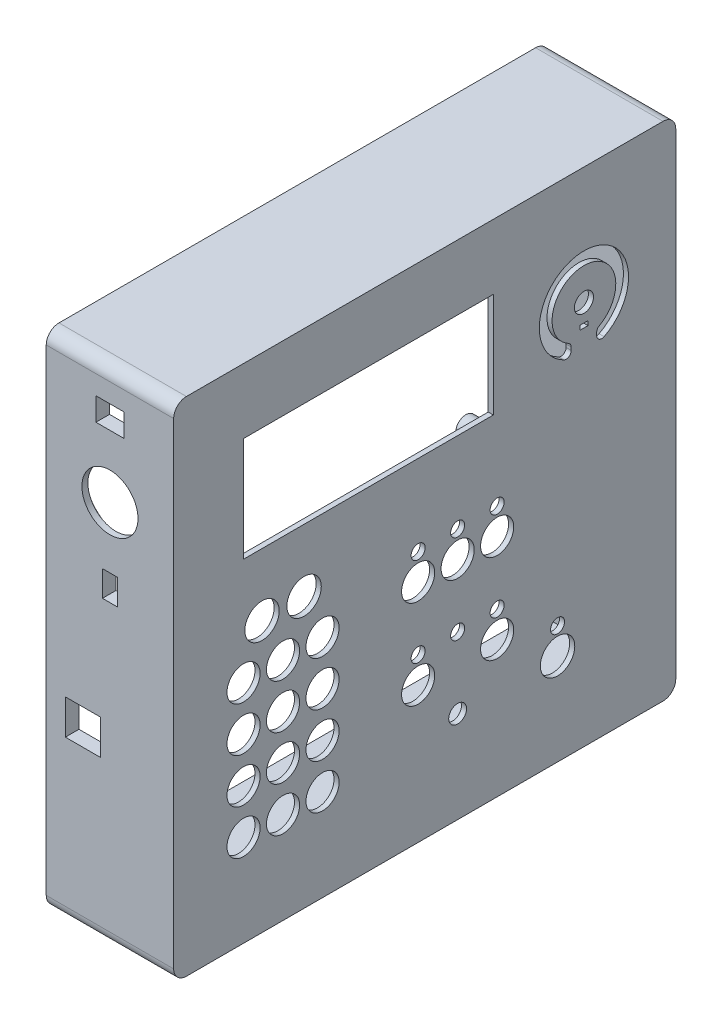
SolidWorks part; units mm, degrees
ref_plane "Front Plane" through (0, 0, 0) normal (0, 0, 1) x (1, 0, 0)
ref_plane "Top Plane" through (0, 0, 0) normal (0, 1, 0) x (1, 0, 0)
ref_plane "Right Plane" through (0, 0, 0) normal (1, 0, 0) x (0, 0, -1)
sketch "Sketch1" plane through (0, 0, 0) normal (1, 0, 0) x (0, 0, -1)
  line L0 (-106.2893, 98.5) -> (-106.2893, -98.5)
  line L1 (-227.2314, 0) -> (0, 0) construction
  line L2 (0, 0) -> (0, 137.3832) construction
  line L3 (-106.2893, -98.5) -> (-303.2893, -98.5)
  line L5 (-106.2893, 98.5) -> (-303.2893, 98.5)
  line L6 (-303.2893, -98.5) -> (-303.2893, 98.5)
  line L7 (-204.7893, 98.5) -> (-204.7893, -98.5) construction
  point P0 (-204.7893, 98.5)
  point P11 (-106.2893, 98.5)
  dimension "D1" = 98.5
  dimension "D2" = 197
  dimension "D3" = 197
  dimension "D4" = 204.7893
extrude "Boss-Extrude1" add sketch "Sketch1" along normal blind 50
sketch "Sketch6" plane through (0, 0, 0) normal (1, 0, 0) x (0, 0, -1)
  line L0 (-106.2893, 98.5) -> (-303.2893, 98.5) construction
  line L5 (0, 0) -> (-397.2484, 0) construction
  line L6 (0, 0) -> (0, 147.2873) construction
  line L7 (-106.2893, 98.5) -> (-303.2893, 98.5) construction
  line L8 (-297.9497, 93.5) -> (-110.9497, 93.5)
  line L9 (-297.9497, 93.5) -> (-297.9497, -93.5)
  line L10 (-297.9497, -93.5) -> (-110.9497, -93.5)
  line L11 (-110.9497, 93.5) -> (-110.9497, -93.5)
  line L13 (-204.4497, 98.5) -> (-204.4497, -141.7446) construction
  point P14 (-204.4497, 98.5)
  dimension "D1" = 187
  dimension "D2" = 187
  dimension "D3" = 93.5
  dimension "D4" = 110.9497
  dimension "D6" = 93.5
extrude "Cut-Extrude1" cut sketch "Sketch6" along normal blind 48
ref_plane "Plane2" through (48, 0, 0) normal (-1, 0, 0) x (0, 0, 1)
sketch "Sketch8" plane through (48, 0, 0) normal (-1, 0, 0) x (0, 0, 1)
  line L0 (0, 0) -> (304.4109, 0) construction
  line L1 (317.8268, 52.5) -> (90.3561, 52.5) construction
  line L2 (226.8693, 32) -> (226.8693, 82.5833) construction
  line L3 (275.8693, 32) -> (177.8693, 32)
  line L4 (275.8693, 32) -> (275.8693, 73)
  line L5 (275.8693, 73) -> (177.8693, 73)
  line L6 (177.8693, 32) -> (177.8693, 73)
  line L7 (276.1193, 22.5) -> (177.6193, 22.5) construction
  line L8 (276.1193, 22.5) -> (276.1193, 82.5) construction
  line L9 (276.1193, 82.5) -> (177.6193, 82.5) construction
  line L10 (177.6193, 22.5) -> (177.6193, 82.5) construction
  line L11 (303.2893, 98.5) -> (303.2893, -98.5) construction
  dimension "D8" = 27.42
  dimension "D1" = 41
  dimension "D2" = 20.5
  dimension "D3" = 98
  dimension "D4" = 98.5
  dimension "D5" = 60
  dimension "D6" = 49.25
  dimension "D7" = 30
  dimension "D10" = 52.5
extrude "Cut-Extrude2" cut sketch "Sketch8" against normal blind 25
sketch "Sketch9" plane through (48, 0, 0) normal (-1, 0, 0) x (0, 0, 1)
  line L0 (275.8693, 52.5) -> (177.8693, 52.5) construction
  line L1 (275.8693, 32) -> (275.8693, 73) construction
  line L2 (177.8693, 32) -> (177.8693, 73) construction
  line L3 (226.8693, 32) -> (226.8693, 73) construction
  line L4 (275.8693, 73) -> (177.8693, 73) construction
  line L5 (0, 0) -> (304.4109, 0) construction
  line L6 (276.1193, 22.5) -> (177.6193, 22.5) construction
  line L7 (177.6193, 22.5) -> (177.6193, 82.5) construction
  circle A0 centre (180.1193, 25) radius 2.35 construction
  circle A1 centre (180.1193, 80) radius 2.35 construction
  circle A2 centre (273.6193, 25) radius 2.35 construction
  circle A3 centre (273.6193, 80) radius 2.35 construction
  circle A4 centre (180.1193, 25) radius 4
  circle A5 centre (180.1193, 80) radius 4
  circle A6 centre (273.6193, 80) radius 4
  circle A7 centre (273.6193, 25) radius 4
  dimension "D1" = 4.7
  dimension "D4" = 8
  dimension "D2" = 2.5
  dimension "D3" = 2.5
extrude "Boss-Extrude2" add sketch "Sketch9" along normal blind 6.5
fillet "Fillet3" radius 1 4 edges at (48, 80, 176.1193) (48, 25, 176.1193) (48, 80, 269.6193) (48, 25, 269.6193)
sketch "Sketch13" plane through (48, 0, 0) normal (-1, 0, 0) x (0, 0, 1)
  line L0 (214.2719, 16.5) -> (214.2719, -90) construction
  line L1 (139.2719, 16.5) -> (289.2719, 16.5) construction
  line L2 (139.2719, 16.5) -> (139.2719, -73.5) construction
  line L3 (139.2719, -73.5) -> (289.2719, -73.5) construction
  line L4 (289.2719, 16.5) -> (289.2719, -73.5) construction
  line L6 (204.7893, 98.4017) -> (204.7893, -98.4255) construction
  line L7 (0, 0) -> (204.7893, -0.0119) construction
  line L8 (139.2719, -28.5) -> (329.9163, -28.5) construction
  line L9 (303.2893, -98.5) -> (106.2893, -98.5) construction
  line L10 (0, 0) -> (0, 42.6543) construction
  line L11 (106.2893, -98.5) -> (106.2893, 98.5) construction
  circle A0 centre (286.7719, 14) radius 4
  circle A1 centre (286.7719, -71) radius 4
  circle A2 centre (141.7719, -71) radius 4
  circle A3 centre (141.7719, 14) radius 4
  dimension "D7" = 8
  dimension "D1" = 150
  dimension "D2" = 90
  dimension "D3" = 75
  dimension "D4" = 70
  dimension "D5" = 2.5
  dimension "D6" = 2.5
  dimension "D8" = 98.5
  dimension "D9" = 9.4826
sketch "Sketch14" plane through (48, 0, 0) normal (-1, 0, 0) x (0, 0, 1)
  line L0 (214.2719, 16.5) -> (214.2719, -73.5) construction
  line L1 (139.2719, 16.5) -> (289.2719, 16.5) construction
  line L2 (139.2719, -73.5) -> (289.2719, -73.5) construction
  line L3 (139.2719, -28.5) -> (289.2719, -28.5) construction
  line L4 (139.2719, 16.5) -> (139.2719, -73.5) construction
  line L5 (289.2719, 16.5) -> (289.2719, -73.5) construction
  circle A0 centre (141.7719, 14) radius 2.45
  circle A5 centre (141.7719, -71) radius 2.45
  circle A6 centre (286.7719, -71) radius 2.45
  circle A7 centre (286.7719, 14) radius 2.45
  dimension "D1" = 4.9
ref_plane "Plane3" through (50, 0, 0) normal (1, 0, 0) x (0, 0, -1)
sketch "Sketch15" plane through (50, 0, 0) normal (1, 0, 0) x (0, 0, -1)
  line L0 (-282.3719, 16.5) -> (-282.3719, -73.5) construction
  line L1 (-139.2719, 16.5) -> (-289.2719, 16.5) construction
  line L2 (-139.2719, -73.5) -> (-289.2719, -73.5) construction
  line L3 (-289.2719, 16.5) -> (-289.2719, -73.5) construction
  line L4 (-289.2719, -69) -> (-139.2719, -69) construction
  line L5 (-139.2719, 16.5) -> (-139.2719, -73.5) construction
  line L6 (-275.8719, -62.5) -> (-275.8719, 0) construction
  line L7 (0, 0) -> (-304.4109, 0) construction
  line L8 (-260.3719, -62.5) -> (-260.3719, 0) construction
  line L9 (-244.8719, -62.5) -> (-244.8719, 0) construction
  line L10 (-282.3719, 7.5) -> (-231.4305, 7.5) construction
  line L11 (-146.1719, -73.5) -> (-146.1719, 16.5) construction
  line L12 (-244.8719, -62.5) -> (-146.1719, -62.5) construction
  line L13 (-275.8719, -10) -> (-153.4, -10) construction
  line L14 (-275.8719, -27.5) -> (-190.7184, -27.5) construction
  line L15 (-275.8719, -45) -> (-176.3719, -45) construction
  line L16 (-275.8719, -62.5) -> (-244.8719, -62.5) construction
  line L17 (-207.3719, -10) -> (-207.3719, -62.5) construction
  line L18 (-176.3719, -10) -> (-176.3719, -62.5) construction
  line L19 (-176.3719, -34.7) -> (-207.3719, -34.7) construction
  line L20 (-191.8719, -10) -> (-191.8719, -45) construction
  line L21 (-207.3719, 0.3) -> (-176.3719, 0.3) construction
  line L22 (-207.3719, 0.3) -> (-207.3719, -10) construction
  line L23 (-191.8719, 0.3) -> (-191.8719, -10) construction
  line L24 (-152.6719, -52.2) -> (-152.6719, -62.5) construction
  line L25 (-191.8719, -34.7) -> (-191.8719, -77.4764) construction
  circle A0 centre (-275.8719, -62.5) radius 6.5
  circle A1 centre (-275.8719, -45) radius 6.5
  circle A2 centre (-275.8719, -27.5) radius 6.5
  circle A3 centre (-275.8719, -10) radius 6.5
  circle A4 centre (-260.3719, -62.5) radius 6.5
  circle A5 centre (-260.3719, -45) radius 6.5
  circle A6 centre (-260.3719, -27.5) radius 6.5
  circle A7 centre (-260.3719, -10) radius 6.5
  circle A8 centre (-244.8719, -62.5) radius 6.5
  circle A9 centre (-244.8719, -45) radius 6.5
  circle A10 centre (-244.8719, -27.5) radius 6.5
  circle A11 centre (-244.8719, -10) radius 6.5
  circle A12 centre (-268.6219, 7.5) radius 6.75
  circle A13 centre (-252.1219, 7.5) radius 6.75
  circle A15 centre (-207.3719, -10) radius 6.5
  circle A16 centre (-191.8719, -10) radius 6.5
  circle A17 centre (-176.3719, -10) radius 6.5
  circle A18 centre (-207.3719, -45) radius 6.5
  circle A19 centre (-176.3719, -45) radius 6.5
  circle A20 centre (-176.3719, -34.7) radius 2.75
  circle A21 centre (-207.3719, -34.7) radius 2.75
  circle A22 centre (-207.3719, 0.3) radius 2.75
  circle A23 centre (-191.8719, 0.3) radius 2.75
  circle A24 centre (-176.3719, 0.3) radius 2.75
  circle A25 centre (-152.6719, -52.2) radius 2.75
  circle A26 centre (-191.8719, -62.5) radius 3.5
  circle A27 centre (-191.8719, -34.7) radius 2.75
  circle A28 centre (-152.6719, -62.5) radius 6.75
  point P23 (-260.3719, -62.5)
  point P33 (-244.8719, -62.5)
  point P44 (-268.6219, 7.5)
  point P45 (-252.1219, 7.5)
  point P56 (-238.3719, -62.5)
  point P57 (-159.1719, -62.5)
  point P64 (-268.6219, 14.25)
  point P84 (-152.6719, -52.2)
  point P87 (-191.8719, -62.5)
  point P90 (-238.3719, -10)
  dimension "D3" = 13
  dimension "D4" = 13
  dimension "D6" = 13
  dimension "D8" = 13
  dimension "D11" = 13
  dimension "D12" = 13
  dimension "D14" = 13
  dimension "D16" = 13
  dimension "D19" = 13
  dimension "D20" = 15.5
  dimension "D21" = 13
  dimension "D22" = 13
  dimension "D23" = 13
  dimension "D29" = 13.5
  dimension "D31" = 10.3
  dimension "D15" = 13
  dimension "D24" = 13
  dimension "D32" = 5.5
  dimension "D33" = 5.5
  dimension "D35" = 5.5
  dimension "D37" = 7
  dimension "D38" = 13.5
  dimension "D1" = 6.9
  dimension "D2" = 4.5
  dimension "D5" = 17.5
  dimension "D7" = 17.5
  dimension "D9" = 17.5
  dimension "D10" = 15.5
  dimension "D13" = 15.5
  dimension "D17" = 37.5
  dimension "D18" = 15.5
  dimension "D25" = 31
  dimension "D26" = 16.5
  dimension "D27" = 8.25
  dimension "D28" = 17.5
  dimension "D30" = 6.9
  dimension "D34" = 10.3
  dimension "D36" = 10.3
extrude "Cut-Extrude7" cut sketch "Sketch15" against normal blind 10
ref_plane "Plane4" through (48, 0, 0) normal (-1, 0, 0) x (0, 0, 1)
sketch "Sketch12" plane through (50, 0, 0) normal (1, 0, 0) x (0, 0, -1)
  line L0 (-142.3193, 52.5) -> (-142.3193, 37.8316) construction
  line L1 (-147.3193, 35.7295) -> (-147.3193, 41.0436)
  line L2 (-137.3193, 35.7295) -> (-137.3193, 41.0436)
  line L4 (-317.8268, 52.5) -> (-90.3561, 52.5) construction
  line L5 (-177.8693, 32) -> (-177.8693, 73) construction
  line L6 (-143.9193, 43.8) -> (-140.7193, 43.8)
  line L7 (-143.9193, 43.8) -> (-143.9193, 45.5)
  line L8 (-143.9193, 45.5) -> (-140.7193, 45.5)
  line L9 (-140.7193, 43.8) -> (-140.7193, 45.5)
  circle A0 centre (-142.3193, 52.5) radius 20 construction
  circle A1 centre (-142.3193, 52.5) radius 3.75
  arc A2 (-137.3193, 41.0436) -> (-147.3193, 41.0436) centre (-142.3193, 52.5) ccw
  arc A3 (-137.3193, 35.7295) -> (-147.3193, 35.7295) centre (-142.3193, 52.5) ccw
  point P8 (-142.3193, 52.5)
  dimension "D2" = 40
  dimension "D3" = 7.5
  dimension "D4" = 25
  dimension "D5" = 35
  dimension "D1" = 35.55
  dimension "D6" = 5
  dimension "D7" = 7
  dimension "D8" = 1.7
  dimension "D9" = 3.2
  dimension "D10" = 1.6
extrude "Cut-Extrude8" cut sketch "Sketch12" against normal blind 10
sketch "Sketch16" plane through (50, 0, 0) normal (1, 0, 0) x (0, 0, -1)
  line L2 (-142.3193, 52.5) -> (-142.3193, -11.4524) construction
  circle A0 centre (-142.3193, 24.5) radius 5
  point P0 (-142.3193, 24.5)
  dimension "D1" = 28
  dimension "D2" = 10
ref_plane "Plane6" through (0, 0, 303.2893) normal (0, 0, 1) x (1, 0, 0)
sketch "Sketch18" plane through (0, 0, 303.2893) normal (0, 0, 1) x (1, 0, 0)
  line L0 (50, 52.5) -> (0, 52.5) construction
  line L1 (0, 98.5) -> (0, -98.5) construction
  circle A1 centre (25, 52.5) radius 11
  dimension "D1" = 22
extrude "Cut-Extrude10" cut sketch "Sketch18" against normal blind 6
sketch "Sketch19" plane through (0, 0, 303.2893) normal (0, 0, 1) x (1, 0, 0)
  line L0 (25, 52.5) -> (25, 94.6537) construction
  line L1 (25, 28.55) -> (25, 17.1024) construction
  line L2 (30.5, 86) -> (19.5, 86)
  line L3 (30.5, 86) -> (30.5, 77)
  line L4 (30.5, 77) -> (19.5, 77)
  line L5 (19.5, 86) -> (19.5, 77)
  line L6 (27.95, 28.55) -> (22.05, 28.55)
  line L7 (25, 81.5) -> (9.3767, 81.5) construction
  line L8 (25, 52.5) -> (25, 28.55) construction
  line L9 (27.95, 28.55) -> (27.95, 18.45)
  line L10 (27.95, 18.45) -> (22.05, 18.45)
  line L11 (22.05, 28.55) -> (22.05, 18.45)
  line L12 (25, 23.5) -> (27.95, 23.5) construction
  point P7 (25, 81.5)
  point P8 (25, 63.3659)
  point P12 (25, 41.5799)
  dimension "D1" = 9
  dimension "D2" = 11
  dimension "D3" = 5.5
  dimension "D4" = 29
  dimension "D5" = 4.5
  dimension "D6" = 5.9
  dimension "D7" = 10.1
  dimension "D8" = 2.95
  dimension "D9" = 29
extrude "Cut-Extrude11" cut sketch "Sketch19" against normal blind 6
fillet "Fillet6" radius 2 4 edges at (49, 35.7295, 137.3193) (49, 35.7295, 147.3193) (49, 41.0436, 137.3193) (49, 41.0436, 147.3193)
ref_plane "Plane7" through (0, 0, 0) normal (-1, 0, 0) x (0, 0, 1)
sketch "Sketch21" plane through (0, 0, 0) normal (-1, 0, 0) x (0, 0, 1)
  line L0 (204.7893, 98.5) -> (204.7893, -98.5) construction
  line L1 (106.2893, 98.5) -> (121.2893, 98.5)
  line L2 (106.2893, 98.5) -> (106.2893, 83.5)
  line L7 (304.4109, 0) -> (106.2893, 0) construction
  line L8 (106.2893, 98.5) -> (106.2893, -98.5) construction
  line L9 (106.2893, -98.5) -> (121.2893, -98.5)
  line L22 (106.2893, -98.5) -> (106.2893, -83.5)
  line L23 (303.2893, -98.5) -> (288.2893, -98.5)
  line L24 (303.2893, -98.5) -> (303.2893, -83.5)
  line L25 (303.2893, 98.5) -> (303.2893, 83.5)
  line L26 (303.2893, 98.5) -> (288.2893, 98.5)
  circle A5 centre (114.2893, 90.5) radius 2.45
  circle A6 centre (114.2893, -90.5) radius 2.45
  arc A7 (106.2893, -83.5) -> (121.2893, -98.5) centre (106.2893, -98.5) cw
  arc A8 (303.2893, -83.5) -> (288.2893, -98.5) centre (303.2893, -98.5) ccw
  circle A9 centre (295.2893, -90.5) radius 2.45
  arc A10 (303.2893, 83.5) -> (288.2893, 98.5) centre (303.2893, 98.5) cw
  circle A11 centre (295.2893, 90.5) radius 2.45
  arc A12 (106.2893, 83.5) -> (121.2893, 98.5) centre (106.2893, 98.5) ccw
  dimension "D1" = 4.9
  dimension "D2" = 15
  dimension "D6" = 8
  dimension "D7" = 8
extrude "Boss-Extrude4" add sketch "Sketch21" against normal blind 5
fillet "Fillet7" radius 5 4 edges at (25, 98.5, 303.2893) (25, 98.5, 106.2893) (25, -98.5, 106.2893) (25, -98.5, 303.2893)
sketch "Sketch22" plane through (0, 0, 303.2893) normal (0, 0, 1) x (1, 0, 0)
  line L0 (50, -98.5) -> (0, -98.5) construction
  line L1 (0, 108.35) -> (0, -108.35) construction
  line L3 (7.5, -36) -> (21.2, -36)
  line L4 (7.5, -36) -> (7.5, -22.3)
  line L5 (7.5, -22.3) -> (21.2, -22.3)
  line L6 (21.2, -36) -> (21.2, -22.3)
  point P0 (7.5, -83)
  point P3 (7.5, -36)
  dimension "D1" = 15.5
  dimension "D2" = 47
  dimension "D3" = 7.5
  dimension "D4" = 7.5
  dimension "D5" = 13.7
  dimension "D6" = 13.7
extrude "Cut-Extrude14" cut sketch "Sketch22" against normal blind 10
ref_plane "Plane8" through (0, 0, 297.9497) normal (0, 0, -1) x (-1, 0, 0)
sketch "Sketch27" plane through (0, 0, 297.9497) normal (0, 0, -1) x (-1, 0, 0)
  circle A1 centre (-25, 52.5) radius 15.1054
extrude "Cut-Extrude17" cut sketch "Sketch27" against normal blind 3
ref_plane "Plane9" through (48, 0, 0) normal (-1, 0, 0) x (0, 0, 1)
sketch "Sketch28" plane through (48, 0, 0) normal (-1, 0, 0) x (0, 0, 1)
  circle A0 centre (180.1193, 80) radius 2.35
  circle A1 centre (180.1193, 25) radius 2.35
  circle A2 centre (273.6193, 80) radius 2.35
  circle A3 centre (273.6193, 25) radius 2.35
  dimension "D1" = 4.7
  dimension "D2" = 4.7
  dimension "D3" = 4.7
  dimension "D4" = 4.7
extrude "Cut-Extrude18" cut sketch "Sketch28" along normal blind 6.5
